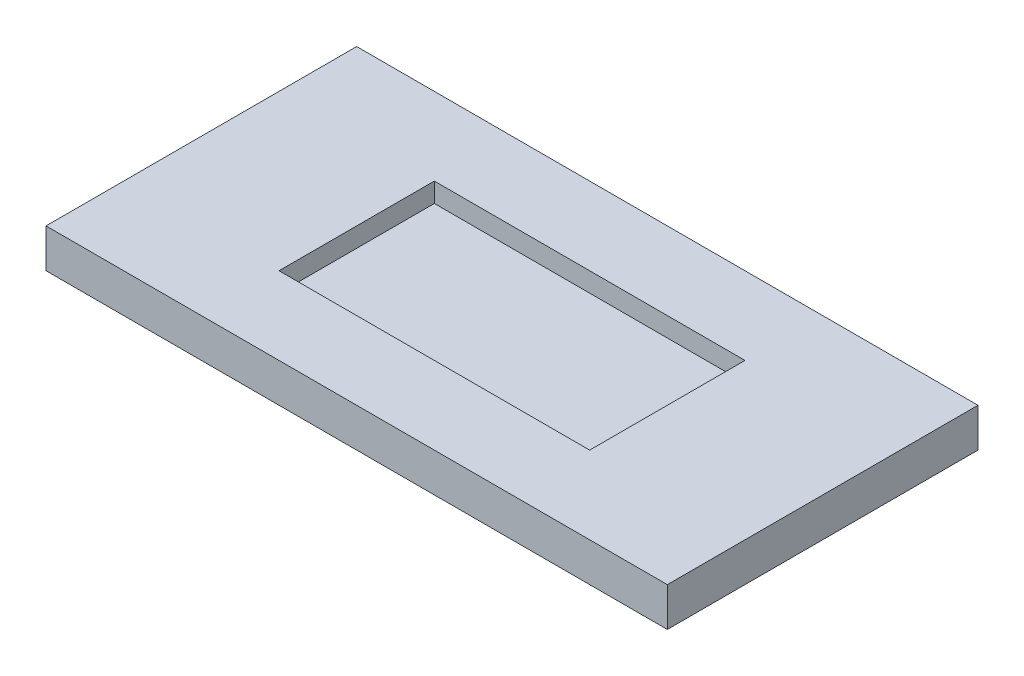
SolidWorks part; units mm, degrees
ref_plane "Спереди" through (0, 0, 0) normal (0, 0, 1) x (1, 0, 0)
ref_plane "Сверху" through (0, 0, 0) normal (0, 1, 0) x (1, 0, 0)
ref_plane "Сбоку" through (0, 0, 0) normal (1, 0, 0) x (0, 0, -1)
sketch "Эскиз1" plane through (0, 0, 0) normal (0, 1, 0) x (1, 0, 0)
  line L1 (-160, -80) -> (160, -80)
  line L2 (-160, -80) -> (-160, 80)
  line L3 (-160, 80) -> (160, 80)
  line L4 (160, -80) -> (160, 80)
  line L5 (-160, -80) -> (160, 80) construction
  line L6 (-160, 80) -> (160, -80) construction
  point P0 (0, 0)
  dimension "D1" = 160
  dimension "D2" = 320
extrude "Бобышка-Вытянуть1" add sketch "Эскиз1" along normal blind 20
sketch "Эскиз2" plane through (0, 20, 0) normal (0, 1, 0) x (1, 0, 0)
  line L1 (-80, -40) -> (80, -40)
  line L2 (-80, -40) -> (-80, 40)
  line L3 (-80, 40) -> (80, 40)
  line L4 (80, -40) -> (80, 40)
  line L5 (-80, -40) -> (80, 40) construction
  line L6 (-80, 40) -> (80, -40) construction
  point P0 (0, 0)
  dimension "D1" = 80
  dimension "D2" = 160
extrude "Вырез-Вытянуть1" cut sketch "Эскиз2" against normal blind 10
